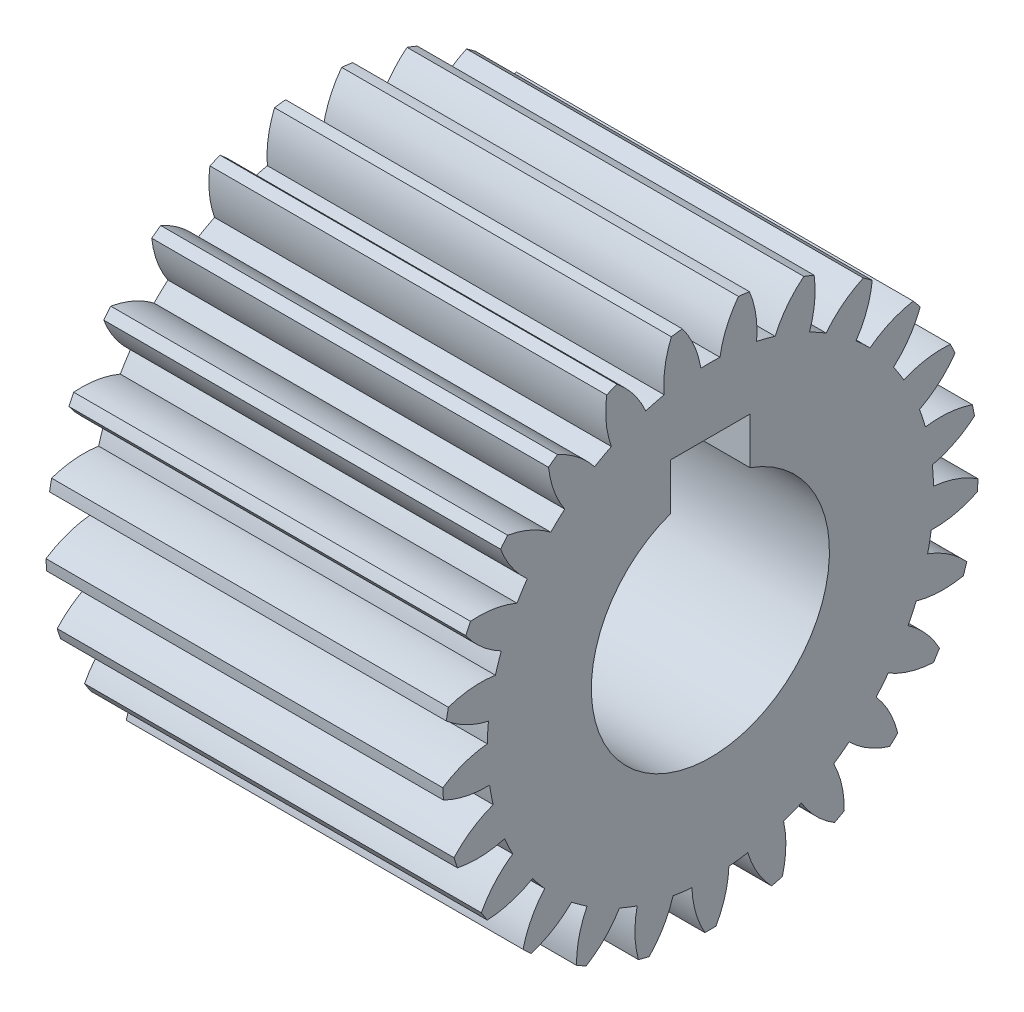
SolidWorks part; units mm, degrees
ref_plane "Plane1" through (0, 0, 0) normal (0, 0, 1) x (1, 0, 0)
ref_plane "Plane2" through (0, 0, 0) normal (0, 1, 0) x (1, 0, 0)
ref_plane "Plane3" through (0, 0, 0) normal (1, 0, 0) x (0, 0, -1)
sketch "HoldingSke" plane through (0, 0, 0) normal (0, 1, 0) x (1, 0, 0)
  line L0 (0, 0) -> (1.8126, -0.8452)
  line L1 (-15, 0) -> (100, 0) construction
  line L2 (0, 0) -> (-2.1039, 2.3779)
  line L3 (0, 0) -> (-11.863, 4.5341)
  line L4 (0, 0) -> (7.8269, 3.6497)
  line L5 (0, 0) -> (-46.8476, -17.4728)
  line L6 (0, 0) -> (-8.2896, -5.593)
  line L7 (-2.1039, 2.3779) -> (8.6586, 51.2059)
  line L8 (-76.2, 54.61) -> (-75.2, 54.61)
  line L9 (-71.009, 38.7566) -> (-53.1078, 45.2721)
  line L10 (-76.2, 71.12) -> (104.1128, 71.12)
  line L11 (0, 0) -> (-10, 0)
  line L12 (-76.2, 101.6) -> (-76.181, 101.6)
  line L13 (24.9733, 27.94) -> (52.9518, 28.4284)
  line L14 (24.9733, 27.94) -> (24.9743, 27.94)
  line L15 (24.9733, 27.94) -> (100.4006, 29.5858)
  line L16 (-63.627, -0.5) -> (-12.827, -0.5)
  circle A0 centre (0, 0) radius 3
  circle A1 centre (0, 0) radius 5.624
  circle A2 centre (0, 0) radius 37.5
  circle A3 centre (0, 0) radius 3
  dimension "MHD" = 11.248
  dimension "Hub_dia" = 75
  dimension "Bore" = 6
  dimension "MBD" = 6
  dimension "Num_teeth" = 25
  dimension "Pitch" = 2
  dimension "Overall_len" = 50
  dimension "Show_teeth" = 25
  dimension "Thickness" = 10
  dimension "OAL" = 50.0001
  dimension "T_dim" = 1
  dimension "Ap" = 20
  dimension "H" = 19.05
  dimension "Pitch_radius" = 180.3128
  dimension "Width" = 10
  dimension "Backlash" = 0.019
  dimension "Addendum_fac" = 1
  dimension "Dedendum_fac" = 1.25
  dimension "Clearance_fac" = 0.25
  dimension "Dedendum_add" = 0.001
  dimension "Module" = 0.5
sketch "BasProSke" plane through (0, 0, 0) normal (0, 1, 0) x (1, 0, 0)
  line L0 (-10, 0) -> (60, 0) construction
  line L1 (0, 0) -> (0, 6.75)
  line L2 (0, 0) -> (10, 0)
  line L3 (10, 0) -> (10, 6.75)
  line L4 (10, 6.75) -> (0, 6.75)
  dimension "Thickness" = 10
  dimension "Diameter" = 13.5
revolve "Base-Revolve" add sketch "BasProSke" angle 360 about L0
sketch "TooCutSke" plane through (0, 0, 0) normal (1, 0, 0) x (0, 0, -1)
  line L1 (0, 0) -> (0, 107) construction
  line L2 (0, 0) -> (-0.4257, 6.2355) construction
  line L3 (0, 0) -> (-1.5641, 12.3809) construction
  line L4 (-0.4257, 6.2355) -> (-0.782, 6.1905) construction
  arc A0 (0.24, 5.6189) -> (-0.24, 5.6189) centre (0, 0) ccw
  arc A1 (0.7251, 6.7365) -> (-0.7251, 6.7365) centre (0, 0) ccw
  circle A2 centre (0, 0) radius 6.25 construction
  circle A3 centre (0, 0) radius 5.8731 construction
  arc A4 (-0.24, 5.6189) -> (-0.7251, 6.7365) centre (-2.7067, 5.2122) ccw
  arc A5 (0.7251, 6.7365) -> (0.24, 5.6189) centre (2.7067, 5.2122) ccw
  dimension "Root_dia" = 11.248
  dimension "Overcut_dia" = 13.5508
  dimension "Pitch_dia" = 12.5
  dimension "Base_dia" = 11.7462
  dimension "Flank_rad" = 2.5
  dimension "Half_ang" = 7.2
  dimension "Half_CT" = 0.3592
extrude "ToothCut" cut sketch "TooCutSke" along normal through all
fillet "Breaks" [suppressed] radius 0.01
fillet "RootFillets" [suppressed] radius 0.126
pattern_circular "TeethCuts" count 25 every 14.4 about axis through (-10, 0, 0) along (1, 0, 0) of "ToothCut", "RootFillets", "Breaks"
sketch "HubNeaOneSke" plane through (0, 0, 0) normal (-1, 0, 0) x (0, 0, 1)
  circle A0 centre (0, 0) radius 5.624
  dimension "Diameter" = 11.248
extrude "HubNearOne" [suppressed] add sketch "HubNeaOneSke" along normal blind 40.0001
sketch "HubNeaBotSke" plane through (0, 0, 0) normal (-1, 0, 0) x (0, 0, 1)
  circle A0 centre (0, 0) radius 5.624
  dimension "Diameter" = 11.248
extrude "HubNearBoth" [suppressed] add sketch "HubNeaBotSke" along normal blind 20
ref_plane "FarPln" through (10, 0, 0) normal (1, 0, 0) x (0, 0, -1)
sketch "HubFarSke" plane through (10, 0, 0) normal (1, 0, 0) x (0, 0, -1)
  circle A0 centre (0, 0) radius 5.624
  dimension "Diameter" = 11.248
extrude "HubFar" [suppressed] add sketch "HubFarSke" along normal blind 20
sketch "BorSke" plane through (0, 0, 0) normal (1, 0, 0) x (0, 0, -1)
  circle A0 centre (0, 0) radius 3
  dimension "Diameter" = 6
extrude "Bore" cut sketch "BorSke" along normal mid plane 100.0001
sketch "KeySke" plane through (0, 0, 0) normal (1, 0, 0) x (0, 0, -1)
  line L0 (-1, 0) -> (-1, 4)
  line L1 (-1, 4) -> (1, 4)
  line L2 (1, 4) -> (1, 0)
  line L3 (0, 0) -> (0, 34) construction
  line L4 (-1, 0) -> (1, 0)
  dimension "Offset" = 4
  dimension "Width" = 2
extrude "Keyway" cut sketch "KeySke" along normal mid plane 100.0001
pattern_circular "Keyway2" [suppressed] count 2 every 90 about axis through (-10, 0, 0) along (1, 0, 0)
equation "' \"Module@HoldingSke\" = 6.35"
equation "' \"Num_teeth@HoldingSke\" = 12"
equation "' \"Ap@HoldingSke\" =  20"
equation "' \"Ap@HoldingSke\" = 20"
equation "' \"Width@HoldingSke\" = 0.5 * 25.4"
equation "' \"Hub_dia@HoldingSke\"= 1 * 25.4"
equation "' \"Hub_dia@HoldingSke\" = 1 * 25.4"
equation "' \"Overall_len@HoldingSke\" = 1.0 * 25.4"
equation "' \"Bore@HoldingSke\" = 0.75 * 25.4"
equation "' \"T_dim@HoldingSke\" = 0.1 * 25.4"
equation "' \"Width@KeySke\" = 0.25 * 25.4"
equation "' \"Show_teeth@HoldingSke\" = 13"
equation "' \"Backlash@HoldingSke\" = 0.009 * 25.4"
equation "' \"Addendum_fac@HoldingSke\" = 1.0"
equation "' \"Dedendum_fac@HoldingSke\" = 1.25"
equation "' \"Dedendum_add@HoldingSke\" = 0.00005 * 25.4"
equation "' \"Clearance_fac@HoldingSke\" = 0.25"
equation "\"Pitch@HoldingSke\" = 1 / \"Module@HoldingSke\""
equation "\"Overcut_dia@TooCutSke\" = (\"Num_teeth@HoldingSke\" + 2 * \"Addendum_fac@HoldingSke\") / \"Pitch@HoldingSke\" + 0.002 * 25.4"
equation "\"Pitch_dia@TooCutSke\" = \"Num_teeth@HoldingSke\" / \"Pitch@HoldingSke\""
equation "\"Base_dia@TooCutSke\" = \"Num_teeth@HoldingSke\" / \"Pitch@HoldingSke\" * cos((\"Ap@HoldingSke\"  * 3.14159265 / 180))"
equation "\"Root_dia@TooCutSke\" = (\"Num_teeth@HoldingSke\" + 2) / \"Pitch@HoldingSke\" - 2 * (\"Addendum_fac@HoldingSke\" + \"Dedendum_fac@HoldingSke\") / \"Pitch@HoldingSke\" - \"Dedendum_add@HoldingSke\" * 2"
equation "\"Half_ang@TooCutSke\" = 180 / \"Num_teeth@HoldingSke\""
equation "\"Half_CT@TooCutSke\" = \"Num_teeth@HoldingSke\" / \"Pitch@HoldingSke\" * sin((3.14159265 / 2 / \"Num_teeth@HoldingSke\")) / 2 - 7 * \"Backlash@HoldingSke\" / 4"
equation "\"Flank_rad@TooCutSke\" = \"Num_teeth@HoldingSke\" / \"Pitch@HoldingSke\" / 5"
equation "\"Radius@RootFillets\" = \"Clearance_fac@HoldingSke\" / \"Pitch@HoldingSke\" + \"Dedendum_add@HoldingSke\""
equation "\"Break_rad@Breaks\" = 0.02 / \"Pitch@HoldingSke\""
equation "\"Thickness@HoldingSke\" = \"Width@HoldingSke\""
equation "\"OAL@HoldingSke\" = \"Thickness@HoldingSke\""
equation "\"MHD@HoldingSke\" = (\"Num_teeth@HoldingSke\" + 2) / \"Pitch@HoldingSke\" - 2 * (\"Addendum_fac@HoldingSke\" + \"Dedendum_fac@HoldingSke\")  / \"Pitch@HoldingSke\" - \"Dedendum_add@HoldingSke\" * 2"
equation "\"MBD@HoldingSke\" = (\"Num_teeth@HoldingSke\" + 2) / \"Pitch@HoldingSke\" - 2 * (\"Addendum_fac@HoldingSke\" + \"Dedendum_fac@HoldingSke\")  / \"Pitch@HoldingSke\" - \"Dedendum_add@HoldingSke\" * 2 - 0.002 * 25.4"
equation "\"MHD@HoldingSke\" = ((sgn( \"MHD@HoldingSke\" - \"Hub_dia@HoldingSke\" )-1)*( \"MHD@HoldingSke\" - \"Hub_dia@HoldingSke\" ))/-2+ \"Hub_dia@HoldingSke\""
equation "\"MBD@HoldingSke\" = ((sgn( \"MBD@HoldingSke\" - \"Bore@HoldingSke\" )-1)*( \"MBD@HoldingSke\" - \"Bore@HoldingSke\" ))/-2+ \"Bore@HoldingSke\""
equation "\"OAL@HoldingSke\" = ((sgn( \"OAL@HoldingSke\" - \"Overall_len@HoldingSke\" )+1)*( \"OAL@HoldingSke\" - \"Overall_len@HoldingSke\" ))/2 + \"Overall_len@HoldingSke\" + 0.000002 * 25.4"
equation "\"Num_teeth@TeethCuts\" = int( \"Show_teeth@HoldingSke\" ) + 1"
equation "\"Num_teeth@TeethCuts\" = ((sgn( \"Num_teeth@TeethCuts\" - \"Num_teeth@HoldingSke\" )-1)*( \"Num_teeth@TeethCuts\" - \"Num_teeth@HoldingSke\" ))/-2+ \"Num_teeth@HoldingSke\""
equation "\"Num_teeth@TeethCuts\" = ((sgn( \"Num_teeth@TeethCuts\" - 2.0)+1)*( \"Num_teeth@TeethCuts\" - 2.0))/2 +2.0"
equation "\"Angle@TeethCuts\" = 360.0 / \"Num_teeth@HoldingSke\""
equation "\"Diameter@BasProSke\" = (\"Num_teeth@HoldingSke\" + 2 * \"Addendum_fac@HoldingSke\") / \"Pitch@HoldingSke\""
equation "\"Thickness@BasProSke\"  = \"Thickness@HoldingSke\""
equation "' \"Fillet_rad@BasProSke\" =  \"Thickness@HoldingSke\" * 0.05"
equation "' \"Fillet_rad@BasProSke\" = \"Thickness@HoldingSke\" * 0.05"
equation "\"MHD@HoldingSke\" = ((sgn( \"MHD@HoldingSke\" - \"Root_dia@TooCutSke\" )-1)*( \"MHD@HoldingSke\" - \"Root_dia@TooCutSke\" ))/-2+ \"Root_dia@TooCutSke\""
equation "\"Diameter@HubNeaOneSke\" = \"MHD@HoldingSke\""
equation "\"Length@HubNearOne\" = \"OAL@HoldingSke\" - \"Thickness@BasProSke\""
equation "\"Diameter@HubNeaBotSke\" = \"MHD@HoldingSke\""
equation "\"Length@HubNearBoth\" = ( \"OAL@HoldingSke\" - \"Thickness@BasProSke\" ) / 2.0"
equation "\"Thickness@FarPln\" = \"Thickness@BasProSke\""
equation "\"Diameter@HubFarSke\" = \"MHD@HoldingSke\""
equation "\"Length@HubFar\" = ( \"OAL@HoldingSke\" - \"Thickness@BasProSke\" ) / 2.0"
equation "\"Diameter@BorSke\" = \"MBD@HoldingSke\""
equation "\"D1@Bore\" = \"OAL@HoldingSke\" * 2.0"
equation "\"D1@Keyway\" = \"OAL@HoldingSke\" * 2.0"
equation "\"Offset@KeySke\" = \"T_dim@HoldingSke\" + \"MBD@HoldingSke\" / 2.0"
